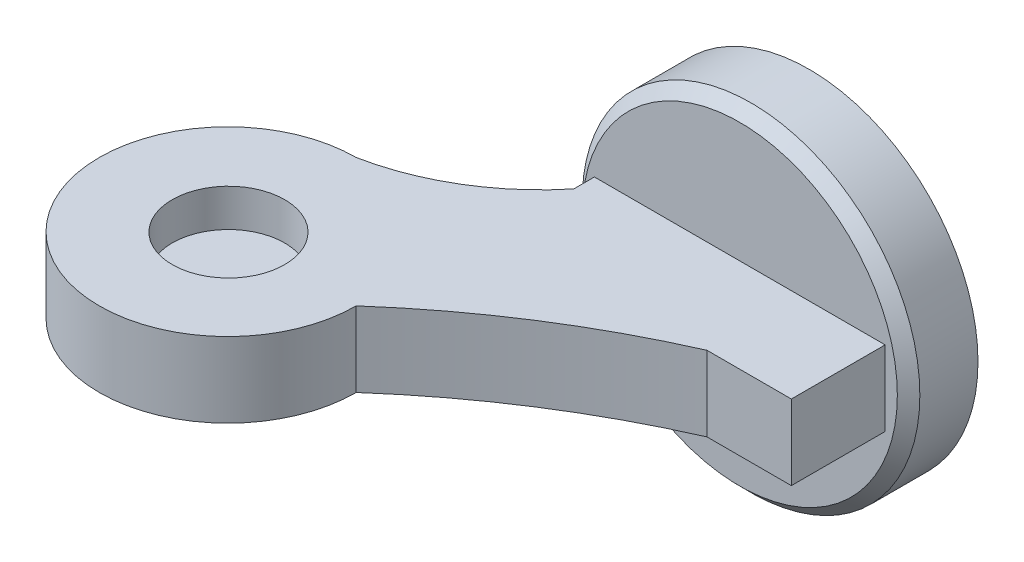
SolidWorks part; units mm, degrees
ref_plane "Front Plane" through (0, 0, 0) normal (0, 0, 1) x (1, 0, 0)
ref_plane "Top Plane" through (0, 0, 0) normal (0, 1, 0) x (1, 0, 0)
ref_plane "Right Plane" through (0, 0, 0) normal (1, 0, 0) x (0, 0, -1)
sketch "Sketch1" plane through (0, 0, 0) normal (0, 0, 1) x (1, 0, 0)
  circle A0 centre (0, 0) radius 90
  dimension "D1" = 180
extrude "Boss-Extrude1" add sketch "Sketch1" along normal blind 37
chamfer "Chamfer1" distance 6 angle 45 1 edges at (90, 0, 37)
sketch "Sketch2" plane through (0, 0, 37) normal (0, 0, 1) x (1, 0, 0)
  line L1 (-77.5, 20) -> (77.5, 20)
  line L2 (-77.5, 20) -> (-77.5, -20)
  line L3 (-77.5, -20) -> (77.5, -20)
  line L4 (77.5, 20) -> (77.5, -20)
  line L5 (0, -20) -> (0, 20) construction
  line L6 (-77.5, 0) -> (77.5, 0) construction
  point P0 (0, 0)
  dimension "D1" = 40
  dimension "D2" = 155
extrude "Boss-Extrude2" add sketch "Sketch2" along normal blind 50
sketch "Sketch3" plane through (0, -20, 0) normal (0, -1, 0) x (1, 0, 0)
  line L0 (-77.5, 87) -> (-77.5, 37) construction
  line L1 (-77.5, 87) -> (77.5, 87) construction
  line L2 (-77.5, 48) -> (-77.5, 87)
  line L3 (-77.5, 87) -> (32.5, 87)
  arc A0 (-77.5, 48) -> (32.5, 87) centre (-68.6761, 197.7402) ccw
  dimension "D3" = 150
  dimension "D1" = 39
  dimension "D2" = 110
extrude "Cut-Extrude1" cut sketch "Sketch3" against normal blind 50
sketch "Sketch4" plane through (0, -20, 0) normal (0, -1, 0) x (-1, 0, 0)
  line L4 (-77.5, -87) -> (-32.5, -87)
  line L5 (77.5, -48) -> (77.5, -37)
  line L6 (77.5, -37) -> (-77.5, -37)
  line L7 (-77.5, -37) -> (-77.5, -87)
  arc A0 (81.5, -160) -> (150, -91.5) centre (150, -160) ccw
  arc A1 (150, -91.5) -> (77.5, -48) centre (174.2724, 31.1207) cw
  arc A2 (-32.5, -87) -> (81.5, -160) centre (-209.9517, -489.63) cw
  arc A4 (77.5, -48) -> (-32.5, -87) centre (68.6761, -197.7402) ccw
  arc A5 (77.5, -48) -> (-32.5, -87) centre (68.6761, -197.7402) ccw
  dimension "D1" = 137
  dimension "D4" = 440
  dimension "D5" = 125
  dimension "D2" = 150
  dimension "D3" = 160
  dimension "D6" = 0
extrude "Boss-Extrude4" add sketch "Sketch4" against normal blind 40 and the other way blind 7.5 draft 70
sketch "Sketch5" plane through (0, -27.5, 0) normal (0, -1, 0) x (1, 0, 0)
  line L0 (-150, 160) -> (-259.1694, 160) construction
  line L1 (-259.1694, 160) -> (-13.8076, 160) construction
  line L2 (-13.8076, 160) -> (-150, 160) construction
  line L3 (-150, 160) -> (-150, 211.2427) construction
  line L4 (-150, 211.2427) -> (-149.1248, 100.9512) construction
  circle A0 centre (-149.5934, 160) radius 40
  spline S0 degree 3 poles (-148.236, 112.1386) (-148.7291, 105.2505) (-149.3264, 98.3718) (-150, 91.5) knots 0 0 0 0 1 1 1 1 construction
  dimension "D1" = 80
extrude "Boss-Extrude5" add sketch "Sketch5" along normal blind 18 draft 28
sketch "Sketch6" plane through (0, -45.5, 0) normal (0, -1, 0) x (-1, 0, 0)
  line L0 (149.5934, -160) -> (149.5934, -222.3433) construction
  arc A1 (149.5934, -190.4292) -> (143.636, -199.5539) centre (151.177, -197.9703) ccw
  circle A2 centre (149.5934, -160) radius 30.4292 construction
  circle A3 centre (149.5934, -160) radius 40 construction
  arc A4 (149.5934, -190.4292) -> (155.5508, -199.5539) centre (148.0097, -197.9703) cw
  dimension "D1" = 7.7055
sketch "Sketch8" plane through (0, -45.5, 0) normal (0, -1, 0) x (1, 0, 0)
  line L0 (-155.5508, 199.5539) -> (-143.636, 199.5539)
  arc A0 (-149.5934, 190.4292) -> (-143.636, 199.5539) centre (-151.177, 197.9703) ccw
  arc A1 (-149.5934, 190.4292) -> (-155.5508, 199.5539) centre (-148.0097, 197.9703) cw
extrude "Cut-Extrude2" cut sketch "Sketch8" against normal up to surface (18 mm away) up to face at (-109.5934, -27.5, 160)
sketch "Sketch9" plane through (0, -45.5, 0) normal (0, -1, 0) x (1, 0, 0)
  line L0 (-149.5934, 160) -> (-149.5934, 222.3433) construction
  circle A0 centre (-149.5934, 195.2134) radius 3
  dimension "D1" = 6
extrude "Cut-Extrude4" cut sketch "Sketch9" against normal blind 20
pattern_circular "CirPattern1" count 12 over 360 about axis through (-149.5934, 0, 160) along (0, 1, 0) of "Cut-Extrude2", "Cut-Extrude4"
sketch "Sketch11" plane through (0, -45.5, 0) normal (0, -1, 0) x (1, 0, 0)
  circle A0 centre (-149.5934, 160) radius 22.5
  dimension "D1" = 45
extrude "Cut-Extrude5" cut sketch "Sketch11" against normal blind 2 draft 45
sketch "Sketch12" plane through (0, -43.5, 0) normal (0, -1, 0) x (1, 0, 0)
  line L0 (-152.7775, 167.8811) -> (-156.8982, 178.0801)
  line L1 (-149.5934, 160) -> (-149.5934, 222.3433) construction
  line L3 (-146.4092, 167.8811) -> (-142.2885, 178.0801)
  arc A0 (-146.4092, 167.8811) -> (-152.7775, 167.8811) centre (-149.5934, 160) ccw
  arc A1 (-142.2885, 178.0801) -> (-156.8982, 178.0801) centre (-149.5934, 160) ccw
  dimension "D1" = 39
  dimension "D2" = 17
  dimension "D3" = 22
  dimension "D4" = 3.1842
extrude "Boss-Extrude6" add sketch "Sketch12" along normal blind 4 draft 20
pattern_circular "CirPattern2" count 4 over 360 about axis through (-149.5934, 0, 160) along (0, 1, 0) of "Boss-Extrude6"
sketch "Sketch14" plane through (0, -43.5, 0) normal (0, -1, 0) x (1, 0, 0)
  circle A0 centre (-149.5934, 160) radius 9.9559
extrude "Boss-Extrude7" add sketch "Sketch14" along normal blind 4
sketch "Sketch16" plane through (0, -47.5, 0) normal (0, -1, 0) x (1, 0, 0)
  circle A0 centre (-149.5934, 160) radius 5
  dimension "D1" = 10
extrude "Cut-Extrude6" cut sketch "Sketch16" against normal up to surface (4 mm away) up to face at (-129.0934, -43.5, 160)
sketch "Sketch17" plane through (0, 20, 0) normal (0, 1, 0) x (1, 0, 0)
  circle A0 centre (-149.5934, -160) radius 30
  dimension "D1" = 60
extrude "Cut-Extrude7" cut sketch "Sketch17" against normal blind 20
sketch "Sketch18" plane through (0, 0, 0) normal (0, 0, -1) x (-1, 0, 0)
  circle A0 centre (0, 0) radius 30
  dimension "D1" = 60
extrude "Cut-Extrude8" cut sketch "Sketch18" against normal blind 20
